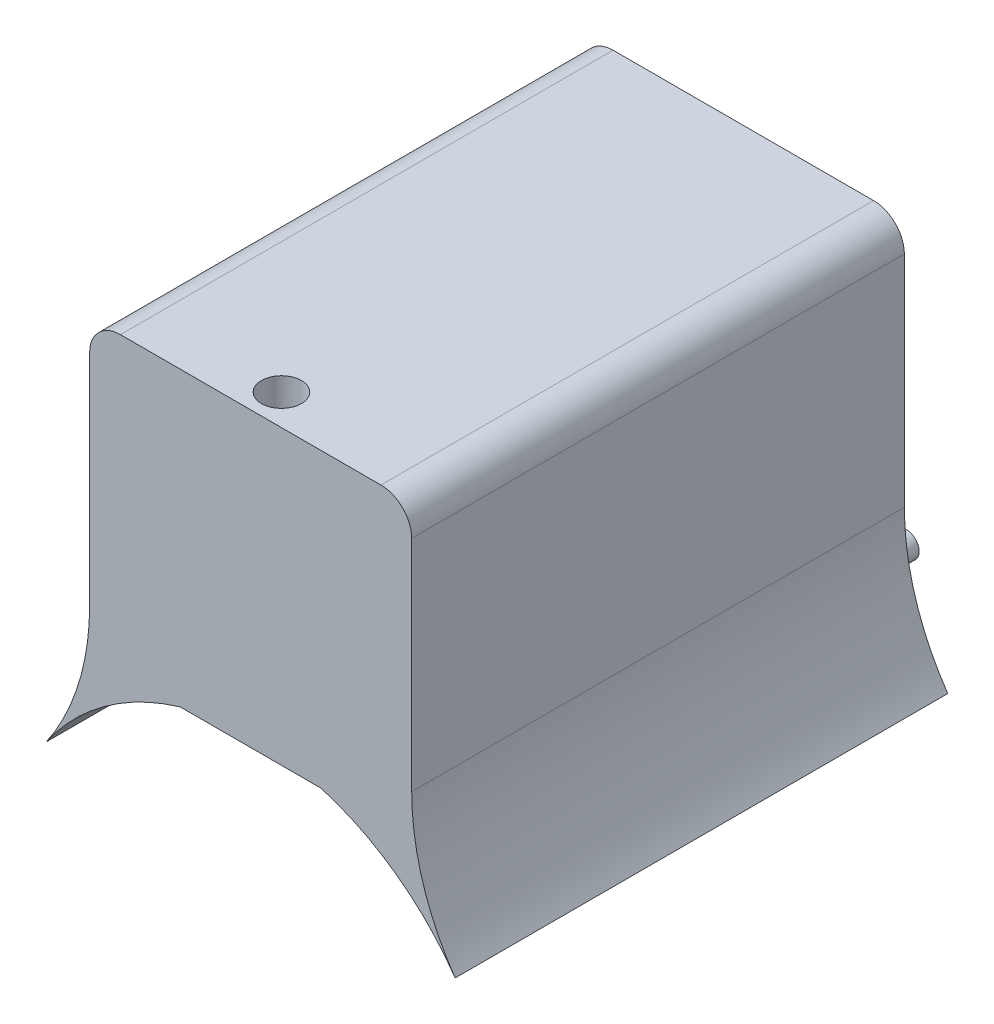
SolidWorks part; units mm, degrees
ref_plane "Front Plane" through (0, 0, 0) normal (0, 0, 1) x (1, 0, 0)
ref_plane "Top Plane" through (0, 0, 0) normal (0, 1, 0) x (1, 0, 0)
ref_plane "Right Plane" through (0, 0, 0) normal (1, 0, 0) x (0, 0, -1)
sketch "Sketch1" plane through (0, 0, 0) normal (0, 0, 1) x (1, 0, 0)
  line L0 (-141.65, 117.2566) -> (-141.65, 119.95)
  line L1 (-139.65, 121.95) -> (-136.9566, 121.95)
  line L2 (-103.0434, 121.95) -> (-100.35, 121.95)
  line L3 (-98.35, 119.95) -> (-98.35, 117.2566)
  line L4 (-93.85, 85.8222) -> (-93.85, 121.45)
  line L5 (-98.85, 126.45) -> (-141.15, 126.45)
  line L6 (-146.15, 121.45) -> (-146.15, 85.8222)
  line L7 (-131.4135, 78.95) -> (-108.5865, 78.95)
  line L8 (-93.85, 85.8222) -> (-93.85, 121.45)
  line L9 (-98.85, 126.45) -> (-141.15, 126.45)
  line L10 (-146.15, 121.45) -> (-146.15, 85.8222)
  line L12 (-98.35, 83.3434) -> (-98.35, 80.65)
  line L13 (-100.35, 78.65) -> (-103.0434, 78.65)
  line L14 (-136.9566, 78.65) -> (-139.65, 78.65)
  line L15 (-141.65, 80.65) -> (-141.65, 119.95)
  line L16 (-98.35, 83.3434) -> (-98.35, 117.2566)
  line L17 (-103.0434, 121.95) -> (-136.9566, 121.95)
  line L18 (-141.65, 117.2566) -> (-141.65, 83.3434)
  line L19 (-136.9566, 78.65) -> (-103.0434, 78.65)
  line L20 (-98.35, 83.3434) -> (-98.35, 117.2566)
  line L21 (-103.0434, 121.95) -> (-136.9566, 121.95)
  line L22 (-141.65, 117.2566) -> (-141.65, 83.3434)
  line L23 (-136.9566, 78.65) -> (-132.3842, 78.65)
  line L24 (-107.6158, 78.65) -> (-103.0434, 78.65)
  arc A0 (-100.35, 121.95) -> (-98.35, 119.95) centre (-100.35, 119.95) cw
  arc A1 (-98.35, 80.65) -> (-100.35, 78.65) centre (-100.35, 80.65) cw
  arc A2 (-139.65, 78.65) -> (-141.65, 80.65) centre (-139.65, 80.65) cw
  arc A3 (-139.65, 121.95) -> (-141.65, 119.95) centre (-139.65, 119.95) ccw
  arc A6 (-93.85, 121.45) -> (-98.85, 126.45) centre (-98.85, 121.45) ccw
  arc A7 (-141.15, 126.45) -> (-146.15, 121.45) centre (-141.15, 121.45) ccw
  arc A8 (-153.1986, 63.1461) -> (-146.15, 85.8222) centre (-186.15, 85.8222) ccw
  arc A9 (-131.4135, 78.95) -> (-153.1986, 63.1461) centre (-120, 40.3) ccw
  arc A10 (-86.8014, 63.1461) -> (-108.5865, 78.95) centre (-120, 40.3) ccw
  arc A11 (-93.85, 85.8222) -> (-86.8014, 63.1461) centre (-53.85, 85.8222) ccw
  arc A12 (-93.85, 121.45) -> (-98.85, 126.45) centre (-98.85, 121.45) ccw
  arc A13 (-141.15, 126.45) -> (-146.15, 121.45) centre (-141.15, 121.45) ccw
  arc A14 (-153.1986, 63.1461) -> (-146.15, 85.8222) centre (-186.15, 85.8222) ccw
  arc A15 (-132.3842, 78.65) -> (-153.1986, 63.1461) centre (-120, 40.3) ccw
  arc A16 (-86.8014, 63.1461) -> (-107.6158, 78.65) centre (-120, 40.3) ccw
  arc A17 (-93.85, 85.8222) -> (-86.8014, 63.1461) centre (-53.85, 85.8222) ccw
  arc A20 (-98.35, 117.2566) -> (-103.0434, 121.95) centre (-120, 100.3) ccw
  arc A21 (-136.9566, 121.95) -> (-141.65, 117.2566) centre (-120, 100.3) ccw
  arc A22 (-141.65, 83.3434) -> (-136.9566, 78.65) centre (-120, 100.3) ccw
  arc A23 (-103.0434, 78.65) -> (-98.35, 83.3434) centre (-120, 100.3) ccw
  dimension "D3" = 2
  dimension "D1" = 0
  dimension "D2" = 0.5
extrude "Boss-Extrude1" add sketch "Sketch1" along normal blind 80
fillet "Fillet1" radius 1 2 edges at (-107.6158, 78.65, 40) (-132.3842, 78.65, 40)
sketch "Sketch4" plane through (0, 0, 0) normal (0, 0, -1) x (-1, 0, 0)
  circle A0 centre (143, 77.3) radius 2.05
  circle A1 centre (97, 77.3) radius 2.05
  circle A2 centre (143, 77.3) radius 2.25 construction
  circle A3 centre (97, 77.3) radius 2.25 construction
  dimension "D1" = 0.2
extrude "Boss-Extrude2" add sketch "Sketch4" along normal blind 3.5
sketch "Sketch5" plane through (0, 0, 80) normal (0, 0, 1) x (1, 0, 0)
  line L4 (-93.85, 85.8222) -> (-93.85, 121.45)
  line L5 (-98.85, 126.45) -> (-141.15, 126.45)
  line L6 (-146.15, 121.45) -> (-146.15, 85.8222)
  line L7 (-131.4135, 78.95) -> (-108.5865, 78.95)
  line L8 (-93.85, 85.8222) -> (-93.85, 121.45)
  line L9 (-98.85, 126.45) -> (-141.15, 126.45)
  line L10 (-146.15, 121.45) -> (-146.15, 85.8222)
  line L11 (-131.4135, 78.95) -> (-108.5865, 78.95)
  arc A6 (-93.85, 121.45) -> (-98.85, 126.45) centre (-98.85, 121.45) ccw
  arc A7 (-141.15, 126.45) -> (-146.15, 121.45) centre (-141.15, 121.45) ccw
  arc A8 (-153.1986, 63.1461) -> (-146.15, 85.8222) centre (-186.15, 85.8222) ccw
  arc A9 (-131.4135, 78.95) -> (-153.1986, 63.1461) centre (-120, 40.3) ccw
  arc A10 (-86.8014, 63.1461) -> (-108.5865, 78.95) centre (-120, 40.3) ccw
  arc A11 (-93.85, 85.8222) -> (-86.8014, 63.1461) centre (-53.85, 85.8222) ccw
  arc A12 (-93.85, 121.45) -> (-98.85, 126.45) centre (-98.85, 121.45) ccw
  arc A13 (-141.15, 126.45) -> (-146.15, 121.45) centre (-141.15, 121.45) ccw
  arc A14 (-153.1986, 63.1461) -> (-146.15, 85.8222) centre (-186.15, 85.8222) ccw
  arc A15 (-131.4135, 78.95) -> (-153.1986, 63.1461) centre (-120, 40.3) ccw
  arc A16 (-86.8014, 63.1461) -> (-108.5865, 78.95) centre (-120, 40.3) ccw
  arc A17 (-93.85, 85.8222) -> (-86.8014, 63.1461) centre (-53.85, 85.8222) ccw
  dimension "D1" = 0
extrude "Boss-Extrude3" add sketch "Sketch5" against normal blind 15
sketch "Sketch6" plane through (0, 126.45, 0) normal (0, 1, 0) x (1, 0, 0)
  circle A0 centre (-120, -75) radius 2.25 construction
  circle A1 centre (-120, -75) radius 2.25 construction
  circle A2 centre (-120, -75) radius 3.25
  dimension "D1" = 6.5
extrude "Cut-Extrude1" cut sketch "Sketch6" against normal offset from surface (44.5 mm away) 3 up to face at (-120, 78.95, 72.5)
ref_plane "Plane1" through (154.609, -389.9, -142.7263) normal (-0.9941, 0, 0.1086) x (0.1086, 0, 0.9941)
sketch "Sketch8" plane through (0, 81.95, 0) normal (0, 1, 0) x (1, 0, 0)
  circle A0 centre (-120, -75) radius 1.65
  dimension "D1" = 3.3
extrude "Cut-Extrude2" cut sketch "Sketch8" against normal through all
